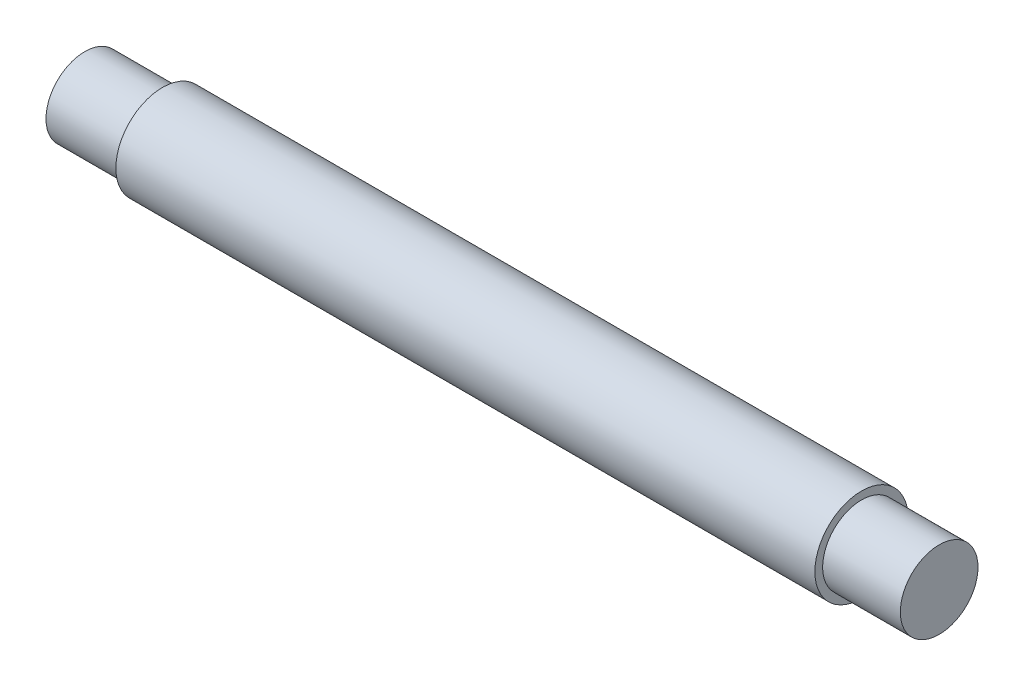
SolidWorks part; units mm, degrees
ref_plane "Front Plane" through (0, 0, 0) normal (0, 0, 1) x (1, 0, 0)
ref_plane "Top Plane" through (0, 0, 0) normal (0, 1, 0) x (1, 0, 0)
ref_plane "Right Plane" through (0, 0, 0) normal (1, 0, 0) x (0, 0, -1)
sketch "Sketch1" plane through (0, 0, 0) normal (1, 0, 0) x (0, 0, -1)
  circle A0 centre (0, 0) radius 6
  dimension "D1" = 12
extrude "Boss-Extrude1" add sketch "Sketch1" along normal blind 110
sketch "Sketch2" plane through (110, 0, 0) normal (1, 0, 0) x (0, 0, -1)
  circle A0 centre (0, 0) radius 5
  dimension "D1" = 10
extrude "Cut-Extrude1" cut sketch "Sketch2" against normal blind 10 flip side to cut
sketch "Sketch3" plane through (0, 0, 0) normal (-1, 0, 0) x (0, 0, 1)
  circle A0 centre (0, 0) radius 5
  dimension "D1" = 10
extrude "Cut-Extrude2" cut sketch "Sketch3" against normal blind 10 flip side to cut
